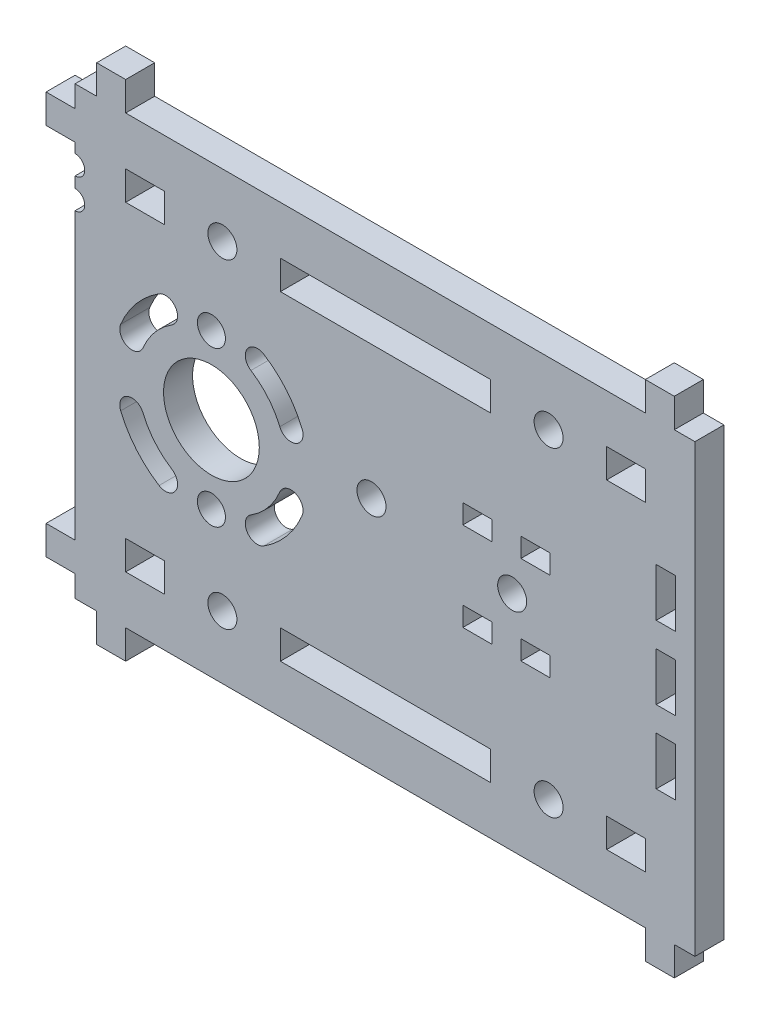
SolidWorks part; units mm, degrees
ref_plane "Front Plane" through (0, 0, 0) normal (0, 0, 1) x (1, 0, 0)
ref_plane "Top Plane" through (0, 0, 0) normal (0, 1, 0) x (1, 0, 0)
ref_plane "Right Plane" through (0, 0, 0) normal (1, 0, 0) x (0, 0, -1)
sketch "Model" plane through (0, 0, 0) normal (0, 0, 1) x (1, 0, 0)
  line L0 (330.5634, 166.1639) -> (330.5634, 120.0639)
  line L1 (328.4315, 169.1639) -> (328.4315, 166.1639)
  line L2 (325.4315, 169.1639) -> (325.4315, 166.1639)
  line L3 (271.6953, 166.1639) -> (271.6953, 169.1639)
  line L4 (268.6953, 166.1639) -> (268.6953, 169.1639)
  line L5 (266.4634, 166.1639) -> (268.6953, 166.1639)
  line L6 (328.4315, 166.1639) -> (330.5634, 166.1639)
  line L7 (271.6953, 166.1639) -> (325.4315, 166.1639)
  line L8 (271.6953, 161.1639) -> (275.6953, 161.1639)
  line L9 (287.6953, 161.1639) -> (309.4315, 161.1639)
  line L10 (321.4315, 161.1639) -> (325.4315, 161.1639)
  line L11 (271.6953, 158.1639) -> (275.6953, 158.1639)
  line L12 (287.6953, 158.1639) -> (309.4315, 158.1639)
  line L13 (321.4315, 158.1639) -> (325.4315, 158.1639)
  line L14 (268.6953, 117.0639) -> (271.6953, 117.0639)
  line L15 (325.4315, 117.0639) -> (328.4315, 117.0639)
  line L16 (328.4315, 117.0639) -> (328.4315, 120.0639)
  line L17 (325.4315, 117.0639) -> (325.4315, 120.0639)
  line L18 (271.6953, 120.0639) -> (271.6953, 117.0639)
  line L19 (268.6953, 120.0639) -> (268.6953, 117.0639)
  line L20 (266.4634, 120.0639) -> (268.6953, 120.0639)
  line L21 (328.4315, 120.0639) -> (330.5634, 120.0639)
  line L22 (271.6953, 120.0639) -> (325.4315, 120.0639)
  line L23 (271.6953, 158.1639) -> (271.6953, 161.1639)
  line L24 (275.6953, 158.1639) -> (275.6953, 161.1639)
  line L25 (287.6953, 158.1639) -> (287.6953, 161.1639)
  line L26 (325.4315, 161.1639) -> (325.4315, 158.1639)
  line L27 (321.4315, 161.1639) -> (321.4315, 158.1639)
  line L28 (309.4315, 161.1639) -> (309.4315, 158.1639)
  line L29 (271.6953, 125.0639) -> (275.6953, 125.0639)
  line L30 (287.6953, 125.0639) -> (309.4315, 125.0639)
  line L31 (321.4315, 125.0639) -> (325.4315, 125.0639)
  line L32 (271.6953, 128.0639) -> (275.6953, 128.0639)
  line L33 (287.6953, 128.0639) -> (309.4315, 128.0639)
  line L34 (321.4315, 128.0639) -> (325.4315, 128.0639)
  line L35 (271.6953, 128.0639) -> (271.6953, 125.0639)
  line L36 (275.6953, 128.0639) -> (275.6953, 125.0639)
  line L37 (287.6953, 128.0639) -> (287.6953, 125.0639)
  line L38 (325.4315, 125.0639) -> (325.4315, 128.0639)
  line L39 (321.4315, 125.0639) -> (321.4315, 128.0639)
  line L40 (309.4315, 125.0639) -> (309.4315, 128.0639)
  line L41 (268.6953, 169.1639) -> (271.6953, 169.1639)
  line L42 (325.4315, 169.1639) -> (328.4315, 169.1639)
  line L125 (266.4634, 120.0639) -> (266.4634, 122.2958)
  line L126 (266.4634, 163.932) -> (266.4634, 166.1639)
  line L127 (263.4634, 160.932) -> (263.4634, 163.932)
  line L128 (266.4634, 163.932) -> (263.4634, 163.932)
  line L129 (266.4634, 160.932) -> (263.4634, 160.932)
  line L130 (263.4634, 125.2958) -> (263.4634, 122.2958)
  line L131 (266.4634, 122.2958) -> (263.4634, 122.2958)
  line L132 (266.4634, 125.2958) -> (263.4634, 125.2958)
  line L141 (266.4634, 125.2958) -> (266.4634, 154.7998)
  line L142 (266.4634, 156.7998) -> (266.4634, 157.9158)
  line L143 (266.4634, 159.9158) -> (266.4634, 160.932)
  line L147 (315.5635, 148.705) -> (315.5635, 146.705)
  line L148 (312.5635, 148.705) -> (312.5635, 146.705)
  line L149 (309.5635, 148.705) -> (309.5635, 146.705)
  line L150 (306.5635, 148.705) -> (306.5635, 146.705)
  line L151 (306.5635, 146.705) -> (309.5635, 146.705)
  line L152 (312.5635, 146.705) -> (315.5635, 146.705)
  line L153 (306.5635, 148.705) -> (309.5635, 148.705)
  line L154 (312.5635, 148.705) -> (315.5635, 148.705)
  line L155 (315.5635, 137.5228) -> (315.5635, 139.5228)
  line L156 (312.5635, 137.5228) -> (312.5635, 139.5228)
  line L157 (309.5635, 137.5228) -> (309.5635, 139.5228)
  line L158 (306.5635, 137.5228) -> (306.5635, 139.5228)
  line L159 (306.5635, 139.5228) -> (309.5635, 139.5228)
  line L160 (312.5635, 139.5228) -> (315.5635, 139.5228)
  line L161 (306.5635, 137.5228) -> (309.5635, 137.5228)
  line L162 (312.5635, 137.5228) -> (315.5635, 137.5228)
  line L191 (328.5635, 153.1639) -> (328.5635, 148.1639)
  line L192 (328.5635, 145.6139) -> (328.5635, 140.6139)
  line L193 (328.5635, 138.0639) -> (328.5635, 133.0639)
  line L194 (326.5635, 153.1639) -> (326.5635, 148.1639)
  line L195 (326.5635, 145.6139) -> (326.5635, 140.6139)
  line L196 (326.5635, 138.0639) -> (326.5635, 133.0639)
  line L197 (326.5635, 153.1639) -> (328.5635, 153.1639)
  line L198 (326.5635, 148.1639) -> (328.5635, 148.1639)
  line L199 (326.5635, 133.0639) -> (328.5635, 133.0639)
  line L200 (326.5635, 138.0639) -> (328.5635, 138.0639)
  line L201 (326.5635, 140.6139) -> (328.5635, 140.6139)
  line L202 (326.5635, 145.6139) -> (328.5635, 145.6139)
  circle A0 centre (280.5634, 143.1139) radius 4.9501
  circle A1 centre (280.5634, 151.1139) radius 1.45
  circle A2 centre (280.5634, 135.1139) radius 1.45
  arc A3 (275.1463, 151.6975) -> (271.1833, 146.9914) centre (280.5634, 143.1139) ccw
  arc A4 (271.1833, 139.2364) -> (275.1463, 134.5304) centre (280.5634, 143.1139) ccw
  arc A5 (289.9436, 146.9914) -> (285.9806, 151.6975) centre (280.5634, 143.1139) ccw
  arc A6 (276.4806, 149.5833) -> (273.4937, 146.0364) centre (280.5634, 143.1139) ccw
  arc A7 (273.4937, 140.1914) -> (276.4806, 136.6446) centre (280.5634, 143.1139) ccw
  arc A8 (284.6463, 136.6446) -> (287.6332, 140.1914) centre (280.5634, 143.1139) ccw
  arc A9 (287.6332, 146.0364) -> (284.6463, 149.5833) centre (280.5634, 143.1139) ccw
  arc A10 (285.9806, 151.6975) -> (284.6463, 149.5833) centre (285.3134, 150.6404) ccw
  arc A11 (287.6332, 146.0364) -> (289.9436, 146.9914) centre (288.7884, 146.5139) ccw
  arc A12 (289.9436, 139.2364) -> (287.6332, 140.1914) centre (288.7884, 139.7139) ccw
  arc A13 (284.6463, 136.6446) -> (285.9806, 134.5304) centre (285.3134, 135.5875) ccw
  arc A14 (275.1463, 134.5304) -> (276.4806, 136.6446) centre (275.8134, 135.5875) ccw
  arc A15 (273.4937, 140.1914) -> (271.1833, 139.2364) centre (272.3385, 139.7139) ccw
  arc A16 (271.1833, 146.9914) -> (273.4937, 146.0364) centre (272.3385, 146.5139) ccw
  arc A17 (276.4806, 149.5833) -> (275.1463, 151.6975) centre (275.8134, 150.6404) ccw
  circle A18 centre (315.4315, 159.6639) radius 1.5
  circle A19 centre (281.6953, 159.6639) radius 1.5
  circle A20 centre (315.4315, 126.5639) radius 1.5
  circle A21 centre (281.6953, 126.5639) radius 1.5
  circle A22 centre (311.6634, 143.1139) radius 1.5
  arc A45 (285.9806, 134.5304) -> (289.9436, 139.2364) centre (280.5634, 143.1139) ccw
  arc A46 (266.4634, 154.7998) -> (266.4634, 156.7998) centre (266.4634, 155.7998) ccw
  arc A47 (266.4634, 157.9158) -> (266.4634, 159.9158) centre (266.4634, 158.9158) ccw
  circle A50 centre (297.1166, 144.3593) radius 1.5
extrude "Boss-Extrude1" add sketch "Model" along normal blind 3
